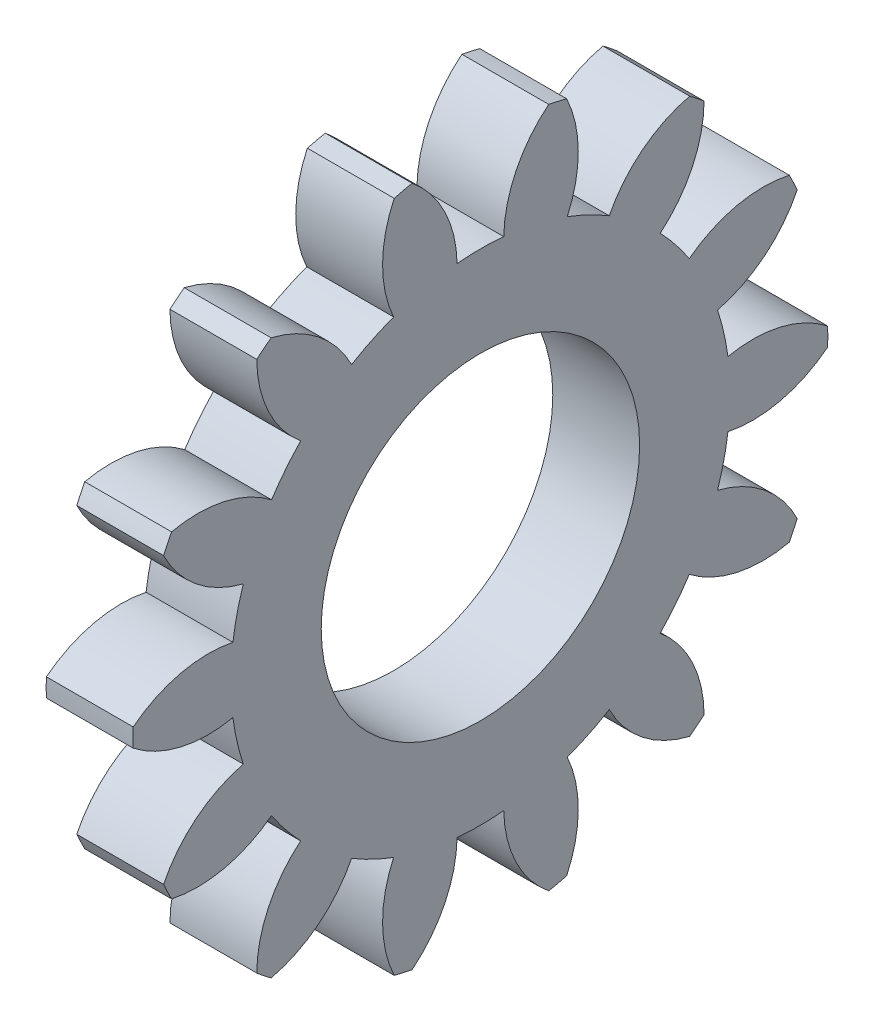
SolidWorks part; units mm, degrees
ref_plane "Plane1" through (0, 0, 0) normal (0, 0, 1) x (1, 0, 0)
ref_plane "Plane2" through (0, 0, 0) normal (0, 1, 0) x (1, 0, 0)
ref_plane "Plane3" through (0, 0, 0) normal (1, 0, 0) x (0, 0, -1)
sketch "HoldingSke" plane through (0, 0, 0) normal (0, 1, 0) x (1, 0, 0)
  line L0 (0, 0) -> (0.3234, -0.0806)
  line L1 (-15, 0) -> (100, 0) construction
  line L2 (0, 0) -> (-2.1039, 2.3779)
  line L3 (0, 0) -> (-11.863, 4.5341)
  line L4 (0, 0) -> (8.3795, 2.0892)
  line L5 (0, 0) -> (-46.8476, -17.4728)
  line L6 (0, 0) -> (-4.9738, -3.3558)
  line L7 (-2.1039, 2.3779) -> (8.6586, 51.2059)
  line L8 (-76.2, 54.61) -> (-72.9, 54.61)
  line L9 (-71.009, 38.7566) -> (-53.1078, 45.2721)
  line L10 (-76.2, 71.12) -> (104.1128, 71.12)
  line L11 (0, 0) -> (-6, 0)
  line L12 (-76.2, 101.6) -> (-76.093, 101.6)
  line L13 (24.9733, 27.94) -> (52.9518, 28.4284)
  line L14 (24.9733, 27.94) -> (24.9743, 27.94)
  line L15 (24.9733, 27.94) -> (100.4006, 29.5858)
  line L16 (-63.627, -3) -> (-12.827, -3)
  circle A0 centre (0, 0) radius 11
  circle A1 centre (0, 0) radius 17.249
  circle A2 centre (0, 0) radius 37.5
  circle A3 centre (0, 0) radius 11
  dimension "MHD" = 34.498
  dimension "Hub_dia" = 75
  dimension "Bore" = 22
  dimension "MBD" = 22
  dimension "Num_teeth" = 14
  dimension "Pitch" = 0.3333
  dimension "Overall_len" = 50
  dimension "Show_teeth" = 14
  dimension "Thickness" = 6
  dimension "OAL" = 50.0001
  dimension "T_dim" = 3.3
  dimension "Ap" = 20
  dimension "H" = 19.05
  dimension "Pitch_radius" = 180.3128
  dimension "Width" = 6
  dimension "Backlash" = 0.107
  dimension "Addendum_fac" = 1
  dimension "Dedendum_fac" = 1.25
  dimension "Clearance_fac" = 0.25
  dimension "Dedendum_add" = 0.001
  dimension "Module" = 3
sketch "BasProSke" plane through (0, 0, 0) normal (0, 1, 0) x (1, 0, 0)
  line L0 (-10, 0) -> (60, 0) construction
  line L1 (0, 0) -> (0, 24)
  line L2 (0, 0) -> (6, 0)
  line L3 (6, 0) -> (6, 24)
  line L4 (6, 24) -> (0, 24)
  dimension "Thickness" = 6
  dimension "Diameter" = 48
revolve "Base-Revolve" add sketch "BasProSke" angle 360 about L0
sketch "TooCutSke" plane through (0, 0, 0) normal (1, 0, 0) x (0, 0, -1)
  line L1 (0, 0) -> (0, 107) construction
  line L2 (0, 0) -> (-2.5383, 20.846) construction
  line L3 (0, 0) -> (-9.2961, 40.729) construction
  line L4 (-2.5383, 20.846) -> (-4.6481, 20.3645) construction
  arc A0 (1.6111, 17.1736) -> (-1.6111, 17.1736) centre (0, 0) ccw
  arc A1 (4.745, 23.5522) -> (-4.745, 23.5522) centre (0, 0) ccw
  circle A2 centre (0, 0) radius 21 construction
  circle A3 centre (0, 0) radius 19.7335 construction
  arc A4 (-1.6111, 17.1736) -> (-4.745, 23.5522) centre (-10.0095, 17.0066) ccw
  arc A5 (4.745, 23.5522) -> (1.6111, 17.1736) centre (10.0095, 17.0066) ccw
  dimension "Root_dia" = 34.498
  dimension "Overcut_dia" = 48.0508
  dimension "Pitch_dia" = 42
  dimension "Base_dia" = 39.4671
  dimension "Flank_rad" = 8.4
  dimension "Half_ang" = 12.857
  dimension "Half_CT" = 2.164
extrude "ToothCut" cut sketch "TooCutSke" along normal through all
fillet "Breaks" [suppressed] radius 0.06
fillet "RootFillets" [suppressed] radius 0.751
pattern_circular "TeethCuts" count 14 every 25.714 about axis through (-10, 0, 0) along (1, 0, 0) of "ToothCut", "RootFillets", "Breaks"
sketch "HubNeaOneSke" plane through (0, 0, 0) normal (-1, 0, 0) x (0, 0, 1)
  circle A0 centre (0, 0) radius 17.249
  dimension "Diameter" = 34.498
extrude "HubNearOne" [suppressed] add sketch "HubNeaOneSke" along normal blind 44.0001
sketch "HubNeaBotSke" plane through (0, 0, 0) normal (-1, 0, 0) x (0, 0, 1)
  circle A0 centre (0, 0) radius 17.249
  dimension "Diameter" = 34.498
extrude "HubNearBoth" [suppressed] add sketch "HubNeaBotSke" along normal blind 22
ref_plane "FarPln" through (6, 0, 0) normal (1, 0, 0) x (0, 0, -1)
sketch "HubFarSke" plane through (6, 0, 0) normal (1, 0, 0) x (0, 0, -1)
  circle A0 centre (0, 0) radius 17.249
  dimension "Diameter" = 34.498
extrude "HubFar" [suppressed] add sketch "HubFarSke" along normal blind 22
sketch "BorSke" plane through (0, 0, 0) normal (1, 0, 0) x (0, 0, -1)
  circle A0 centre (0, 0) radius 11
  dimension "Diameter" = 22
extrude "Bore" cut sketch "BorSke" along normal mid plane 100.0001
sketch "KeySke" plane through (0, 0, 0) normal (1, 0, 0) x (0, 0, -1)
  line L0 (-4, 0) -> (-4, 14.3)
  line L1 (-4, 14.3) -> (4, 14.3)
  line L2 (4, 14.3) -> (4, 0)
  line L3 (0, 0) -> (0, 34) construction
  line L4 (-4, 0) -> (4, 0)
  dimension "Offset" = 14.3
  dimension "Width" = 8
extrude "Keyway" [suppressed] cut sketch "KeySke" along normal mid plane 100.0001
pattern_circular "Keyway2" [suppressed] count 2 every 90 about axis through (-10, 0, 0) along (1, 0, 0)
equation "' \"Module@HoldingSke\" = 6.35"
equation "' \"Num_teeth@HoldingSke\" = 12"
equation "' \"Ap@HoldingSke\" =  20"
equation "' \"Ap@HoldingSke\" = 20"
equation "' \"Width@HoldingSke\" = 0.5 * 25.4"
equation "' \"Hub_dia@HoldingSke\"= 1 * 25.4"
equation "' \"Hub_dia@HoldingSke\" = 1 * 25.4"
equation "' \"Overall_len@HoldingSke\" = 1.0 * 25.4"
equation "' \"Bore@HoldingSke\" = 0.75 * 25.4"
equation "' \"T_dim@HoldingSke\" = 0.1 * 25.4"
equation "' \"Width@KeySke\" = 0.25 * 25.4"
equation "' \"Show_teeth@HoldingSke\" = 13"
equation "' \"Backlash@HoldingSke\" = 0.009 * 25.4"
equation "' \"Addendum_fac@HoldingSke\" = 1.0"
equation "' \"Dedendum_fac@HoldingSke\" = 1.25"
equation "' \"Dedendum_add@HoldingSke\" = 0.00005 * 25.4"
equation "' \"Clearance_fac@HoldingSke\" = 0.25"
equation "\"Pitch@HoldingSke\" = 1 / \"Module@HoldingSke\""
equation "\"Overcut_dia@TooCutSke\" = (\"Num_teeth@HoldingSke\" + 2 * \"Addendum_fac@HoldingSke\") / \"Pitch@HoldingSke\" + 0.002 * 25.4"
equation "\"Pitch_dia@TooCutSke\" = \"Num_teeth@HoldingSke\" / \"Pitch@HoldingSke\""
equation "\"Base_dia@TooCutSke\" = \"Num_teeth@HoldingSke\" / \"Pitch@HoldingSke\" * cos((\"Ap@HoldingSke\"  * 3.14159265 / 180))"
equation "\"Root_dia@TooCutSke\" = (\"Num_teeth@HoldingSke\" + 2) / \"Pitch@HoldingSke\" - 2 * (\"Addendum_fac@HoldingSke\" + \"Dedendum_fac@HoldingSke\") / \"Pitch@HoldingSke\" - \"Dedendum_add@HoldingSke\" * 2"
equation "\"Half_ang@TooCutSke\" = 180 / \"Num_teeth@HoldingSke\""
equation "\"Half_CT@TooCutSke\" = \"Num_teeth@HoldingSke\" / \"Pitch@HoldingSke\" * sin((3.14159265 / 2 / \"Num_teeth@HoldingSke\")) / 2 - 7 * \"Backlash@HoldingSke\" / 4"
equation "\"Flank_rad@TooCutSke\" = \"Num_teeth@HoldingSke\" / \"Pitch@HoldingSke\" / 5"
equation "\"Radius@RootFillets\" = \"Clearance_fac@HoldingSke\" / \"Pitch@HoldingSke\" + \"Dedendum_add@HoldingSke\""
equation "\"Break_rad@Breaks\" = 0.02 / \"Pitch@HoldingSke\""
equation "\"Thickness@HoldingSke\" = \"Width@HoldingSke\""
equation "\"OAL@HoldingSke\" = \"Thickness@HoldingSke\""
equation "\"MHD@HoldingSke\" = (\"Num_teeth@HoldingSke\" + 2) / \"Pitch@HoldingSke\" - 2 * (\"Addendum_fac@HoldingSke\" + \"Dedendum_fac@HoldingSke\")  / \"Pitch@HoldingSke\" - \"Dedendum_add@HoldingSke\" * 2"
equation "\"MBD@HoldingSke\" = (\"Num_teeth@HoldingSke\" + 2) / \"Pitch@HoldingSke\" - 2 * (\"Addendum_fac@HoldingSke\" + \"Dedendum_fac@HoldingSke\")  / \"Pitch@HoldingSke\" - \"Dedendum_add@HoldingSke\" * 2 - 0.002 * 25.4"
equation "\"MHD@HoldingSke\" = ((sgn( \"MHD@HoldingSke\" - \"Hub_dia@HoldingSke\" )-1)*( \"MHD@HoldingSke\" - \"Hub_dia@HoldingSke\" ))/-2+ \"Hub_dia@HoldingSke\""
equation "\"MBD@HoldingSke\" = ((sgn( \"MBD@HoldingSke\" - \"Bore@HoldingSke\" )-1)*( \"MBD@HoldingSke\" - \"Bore@HoldingSke\" ))/-2+ \"Bore@HoldingSke\""
equation "\"OAL@HoldingSke\" = ((sgn( \"OAL@HoldingSke\" - \"Overall_len@HoldingSke\" )+1)*( \"OAL@HoldingSke\" - \"Overall_len@HoldingSke\" ))/2 + \"Overall_len@HoldingSke\" + 0.000002 * 25.4"
equation "\"Num_teeth@TeethCuts\" = int( \"Show_teeth@HoldingSke\" ) + 1"
equation "\"Num_teeth@TeethCuts\" = ((sgn( \"Num_teeth@TeethCuts\" - \"Num_teeth@HoldingSke\" )-1)*( \"Num_teeth@TeethCuts\" - \"Num_teeth@HoldingSke\" ))/-2+ \"Num_teeth@HoldingSke\""
equation "\"Num_teeth@TeethCuts\" = ((sgn( \"Num_teeth@TeethCuts\" - 2.0)+1)*( \"Num_teeth@TeethCuts\" - 2.0))/2 +2.0"
equation "\"Angle@TeethCuts\" = 360.0 / \"Num_teeth@HoldingSke\""
equation "\"Diameter@BasProSke\" = (\"Num_teeth@HoldingSke\" + 2 * \"Addendum_fac@HoldingSke\") / \"Pitch@HoldingSke\""
equation "\"Thickness@BasProSke\"  = \"Thickness@HoldingSke\""
equation "' \"Fillet_rad@BasProSke\" =  \"Thickness@HoldingSke\" * 0.05"
equation "' \"Fillet_rad@BasProSke\" = \"Thickness@HoldingSke\" * 0.05"
equation "\"MHD@HoldingSke\" = ((sgn( \"MHD@HoldingSke\" - \"Root_dia@TooCutSke\" )-1)*( \"MHD@HoldingSke\" - \"Root_dia@TooCutSke\" ))/-2+ \"Root_dia@TooCutSke\""
equation "\"Diameter@HubNeaOneSke\" = \"MHD@HoldingSke\""
equation "\"Length@HubNearOne\" = \"OAL@HoldingSke\" - \"Thickness@BasProSke\""
equation "\"Diameter@HubNeaBotSke\" = \"MHD@HoldingSke\""
equation "\"Length@HubNearBoth\" = ( \"OAL@HoldingSke\" - \"Thickness@BasProSke\" ) / 2.0"
equation "\"Thickness@FarPln\" = \"Thickness@BasProSke\""
equation "\"Diameter@HubFarSke\" = \"MHD@HoldingSke\""
equation "\"Length@HubFar\" = ( \"OAL@HoldingSke\" - \"Thickness@BasProSke\" ) / 2.0"
equation "\"Diameter@BorSke\" = \"MBD@HoldingSke\""
equation "\"D1@Bore\" = \"OAL@HoldingSke\" * 2.0"
equation "\"D1@Keyway\" = \"OAL@HoldingSke\" * 2.0"
equation "\"Offset@KeySke\" = \"T_dim@HoldingSke\" + \"MBD@HoldingSke\" / 2.0"
